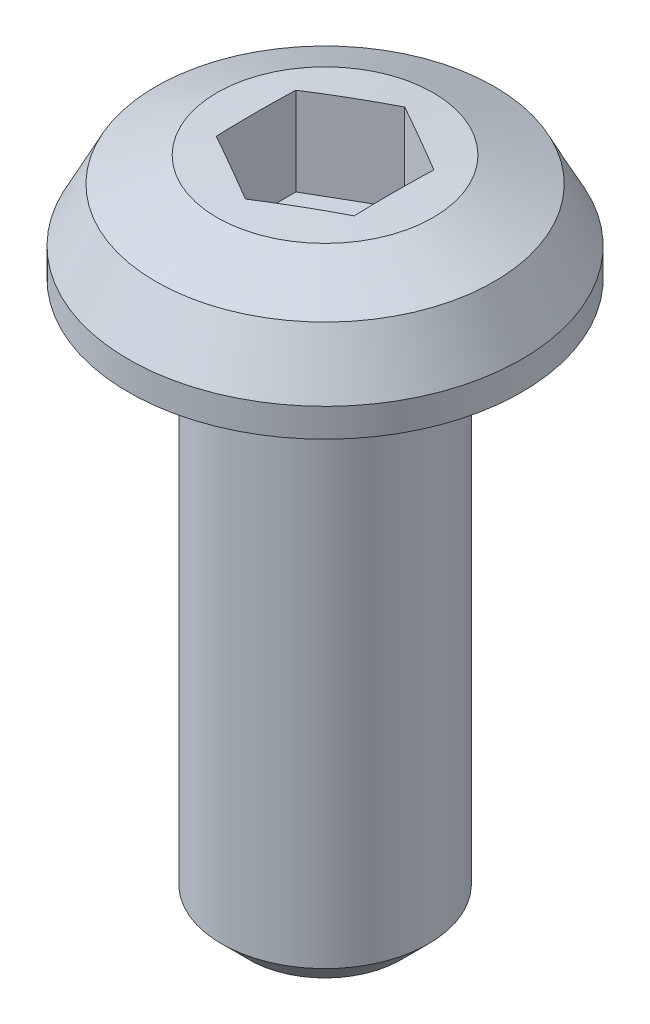
SolidWorks part; units mm, degrees
ref_plane "Front Plane" through (0, 0, 0) normal (0, 0, 1) x (1, 0, 0)
ref_plane "Top Plane" through (0, 0, 0) normal (0, 1, 0) x (1, 0, 0)
ref_plane "Right Plane" through (0, 0, 0) normal (1, 0, 0) x (0, 0, -1)
sketch "Sketch1" plane through (0, 0, 0) normal (0, 0, 1) x (1, 0, 0)
  line L0 (0, -8) -> (1.1, -8)
  line L1 (1.1, -8) -> (1.5, -7.6)
  line L2 (1.5, -7.6) -> (1.5, 0)
  line L3 (1.5, 0) -> (2.85, 0)
  line L4 (2.85, 0) -> (2.85, 0.4125)
  line L5 (2.85, 0.4125) -> (2.451, 1.188)
  line L6 (2.451, 1.188) -> (1.5675, 1.551)
  line L7 (1.5675, 1.551) -> (0, 1.65)
  line L8 (0, 1.65) -> (0, -8)
  line L9 (0, -10) -> (0, 1000) construction
revolve "Revolve1" add sketch "Sketch1" angle 360 about L9
cosmetic thread "Cosmetic Thread1"
ref_plane "Plane1" through (0, 1.65, 0) normal (0, 1, 0) x (1, 0, 0)
sketch "Sketch2" plane through (0, 1.65, 0) normal (0, 1, 0) x (1, 0, 0)
  line L0 (1, -0.5774) -> (0, -1.1547)
  line L1 (0, -1.1547) -> (-1, -0.5774)
  line L2 (-1, -0.5774) -> (-1, 0.5774)
  line L3 (-1, 0.5774) -> (0, 1.1547)
  line L4 (0, 1.1547) -> (1, 0.5774)
  line L5 (1, 0.5774) -> (1, -0.5774)
extrude "Cut-Extrude1" cut sketch "Sketch2" against normal blind 1.35
